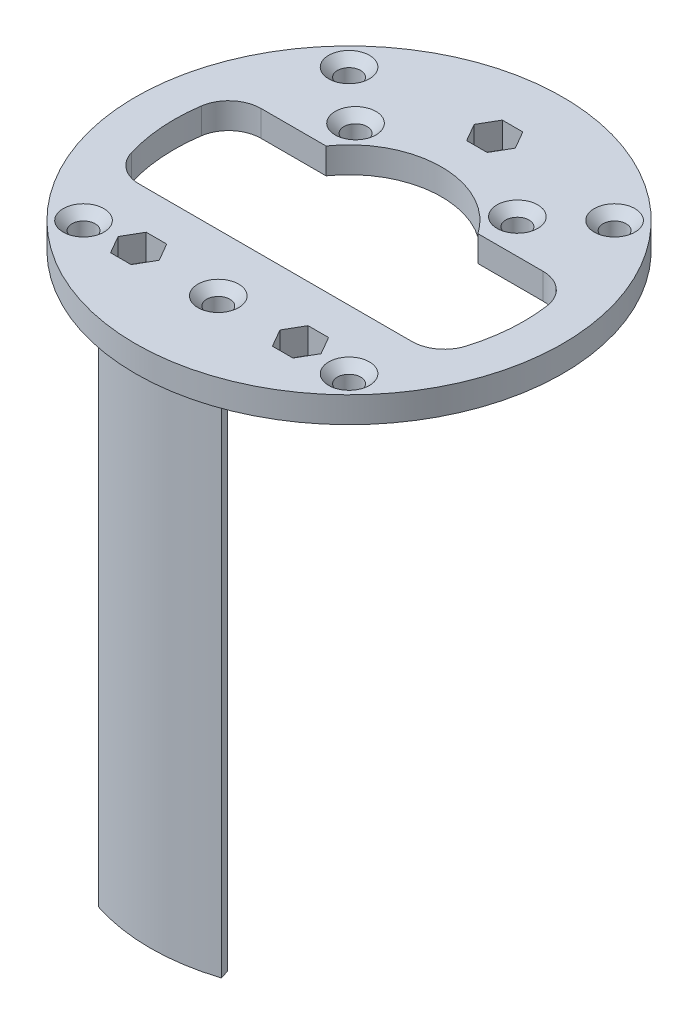
SolidWorks part; units mm, degrees
material "PEI"
ref_plane "Front Plane" through (0, 0, 0) normal (0, 0, 1) x (1, 0, 0)
ref_plane "Top Plane" through (0, 0, 0) normal (0, 1, 0) x (1, 0, 0)
ref_plane "Right Plane" through (0, 0, 0) normal (1, 0, 0) x (0, 0, -1)
sketch "Sketch1" plane through (0, 0, 0) normal (0, 1, 0) x (1, 0, 0)
  circle A0 centre (0, 0) radius 33
  circle A1 centre (0, 0) radius 27
  dimension "D1" = 66
  dimension "D2" = 6
extrude "Boss-Extrude1" add sketch "Sketch1" along normal blind 4
sketch "Sketch2" plane through (0, 4, 0) normal (0, 1, 0) x (1, 0, 0)
  line L0 (-24.5, -11.3468) -> (24.5, -11.3468)
  line L1 (-25.7325, 8.1755) -> (-11.7325, 8.1755)
  line L2 (0, 0) -> (7.7557, 0) construction
  line L3 (11.7325, 8.1755) -> (25.7325, 8.1755)
  line L4 (-20.5061, 20.5061) -> (0, 0) construction
  line L5 (-12.5, 13.5) -> (12.5, 13.5) construction
  circle A0 centre (0, 22.5) radius 2.25 construction
  circle A1 centre (-12.5, -20) radius 2.25 construction
  circle A2 centre (12.5, -20) radius 2.25 construction
  circle A4 centre (-12.5, 13.5) radius 1.5
  circle A6 centre (0, 0) radius 27 construction
  arc A8 (-11.7325, 8.1755) -> (11.7325, 8.1755) centre (0, 0) cw
  arc A9 (25.7325, 8.1755) -> (-25.7325, 8.1755) centre (0, 0) ccw
  arc A10 (24.5, -11.3468) -> (-24.5, -11.3468) centre (0, 0) cw
  circle A11 centre (12.5, 13.5) radius 1.5
  circle A12 centre (0, 0) radius 29 construction
  circle A13 centre (0, 0) radius 33 construction
  circle A14 centre (-20.5061, 20.5061) radius 1.75 construction
  circle A15 centre (20.5061, 20.5061) radius 1.75 construction
  circle A16 centre (20.5061, -20.5061) radius 1.75 construction
  circle A17 centre (-20.5061, -20.5061) radius 1.75 construction
  circle A18 centre (0, -20.2) radius 1.5
  point P15 (0, 13.5)
  point P19 (0, 0)
  point P44 (0, 0)
  circle M2 centre (0, 0) radius 27
  dimension "D5" = 4.5
  dimension "D6" = 4.5
  dimension "D7" = 4.5
  dimension "D12" = 14.3
  dimension "D16" = 3.5
  dimension "D11" = 3
  dimension "D1" = 25
  dimension "D2" = 12.5
  dimension "D3" = 22.5
  dimension "D4" = 20
  dimension "D14" = 4
  dimension "D15" = 135
  dimension "D8" = 14
  dimension "D9" = 14
  dimension "D10" = 49
  dimension "D18" = 25
  dimension "D19" = 20.2
  dimension "D13" = 13.5
  dimension "D17" = 4
extrude "Saliente-Extruir1" add sketch "Sketch2" against normal up to surface (4 mm away) contours L1 A8 L3 M2 | L0 M2 up to face at (0, 0, 33)
sketch "Croquis1" plane through (0, 4, 0) normal (0, 1, 0) x (1, 0, 0)
  line L1 (-9.3246, -20) -> (-10.9123, -17.25)
  line L2 (-10.9123, -17.25) -> (-14.0877, -17.25)
  line L3 (-14.0877, -17.25) -> (-15.6754, -20)
  line L4 (-15.6754, -20) -> (-14.0877, -22.75)
  line L5 (-14.0877, -22.75) -> (-10.9123, -22.75)
  line L6 (-10.9123, -22.75) -> (-9.3246, -20)
  line L7 (15.6754, -20) -> (14.0877, -17.25)
  line L8 (14.0877, -17.25) -> (10.9123, -17.25)
  line L9 (10.9123, -17.25) -> (9.3246, -20)
  line L10 (9.3246, -20) -> (10.9123, -22.75)
  line L11 (10.9123, -22.75) -> (14.0877, -22.75)
  line L12 (14.0877, -22.75) -> (15.6754, -20)
  line L13 (3.1754, 22.5) -> (1.5877, 25.25)
  line L14 (1.5877, 25.25) -> (-1.5877, 25.25)
  line L15 (-1.5877, 25.25) -> (-3.1754, 22.5)
  line L16 (-3.1754, 22.5) -> (-1.5877, 19.75)
  line L17 (-1.5877, 19.75) -> (1.5877, 19.75)
  line L18 (1.5877, 19.75) -> (3.1754, 22.5)
  circle A0 centre (-20.5061, 20.5061) radius 1.75 construction
  circle A1 centre (-20.5061, 20.5061) radius 1.75
  circle A4 centre (20.5061, 20.5061) radius 1.75 construction
  circle A5 centre (20.5061, 20.5061) radius 1.75
  circle A6 centre (-12.5, -20) radius 2.75 construction
  circle A7 centre (12.5, -20) radius 2.75 construction
  circle A8 centre (0, 22.5) radius 2.75 construction
  circle A16 centre (-20.5061, -20.5061) radius 1.75 construction
  circle A17 centre (-20.5061, -20.5061) radius 1.75
  circle A18 centre (20.5061, -20.5061) radius 1.75 construction
  circle A19 centre (20.5061, -20.5061) radius 1.75
  dimension "D1" = 5.5
  dimension "D2" = 5.5
  dimension "D3" = 5.5
extrude "Cortar-Extruir1" cut sketch "Croquis1" against normal up to next
hole_wizard "CSK for M3 Flat Head Machine Screw1" positions "Sketch4" profile "Sketch5" countersink size "M3" standard "ANSI Metric" end condition through all
sketch "Sketch4" plane through (0, 4, 0) normal (0, 1, 0) x (1, 0, 0)
  point P0 (-20.5061, 20.5061)
  point P3 (20.5061, 20.5061)
  point P6 (20.5061, -20.5061)
  point P9 (-20.5061, -20.5061)
sketch "Sketch5" plane through (-20.5061, 4, -20.5061) normal (1, 0, 0) x (0, 0, 1)
  line L0 (0, 0) -> (0, 4)
  line L1 (0, 4) -> (1.8, 4)
  line L2 (1.8, 4) -> (1.8, 1.35)
  line L3 (1.8, 1.35) -> (3.15, 0)
  line L5 (3.15, 0) -> (0, 0)
  line L6 (-1.8, 1.35) -> (-3.15, 0) construction
  line L11 (0, -6.35) -> (0, 107.95) construction
  dimension "Thru Hole Dia." = 3.6
  dimension "Thru Hole Depth" = 4
  dimension "Near C'Sink Dia." = 6.3
  dimension "Near C'Sink Angle" = 90
hole_wizard "CSK for M3 Flat Head Machine Screw2" positions "Sketch6" profile "Sketch7" countersink size "M3" standard "ANSI Metric" end condition through all
sketch "Sketch6" plane through (0, 4, 0) normal (0, 1, 0) x (1, 0, 0)
  point P12 (-12.5, 13.5)
  point P15 (12.5, 13.5)
  point P18 (0, -20.2)
sketch "Sketch7" plane through (-12.5, 4, -13.5) normal (1, 0, 0) x (0, 0, 1)
  line L0 (0, 0) -> (0, 4)
  line L1 (0, 4) -> (1.8, 4)
  line L2 (1.8, 4) -> (1.8, 1.35)
  line L3 (1.8, 1.35) -> (3.15, 0)
  line L5 (3.15, 0) -> (0, 0)
  line L6 (-1.8, 1.35) -> (-3.15, 0) construction
  line L11 (0, -6.35) -> (0, 107.95) construction
  dimension "Thru Hole Dia." = 3.6
  dimension "Thru Hole Depth" = 4
  dimension "Near C'Sink Dia." = 6.3
  dimension "Near C'Sink Angle" = 90
fillet "Fillet1" radius 5 4 edges at (-25.7325, 2, -8.1755) (25.7325, 2, -8.1755) (24.5, 2, 11.3468) (-24.5, 2, 11.3468)
sketch "Sketch8" plane through (0, 0, 0) normal (0, -1, 0) x (-1, 0, 0)
  line L0 (0, 0) -> (9.4868, -29.1974) construction
  line L1 (0, 0) -> (-9.4868, -29.1974) construction
  line L2 (-9.4868, -29.1974) -> (-9.0233, -27.7709)
  line L3 (9.4868, -29.1974) -> (9.0233, -27.7709)
  line L4 (0, 0) -> (0, -16.5239) construction
  arc A0 (9.4868, -29.1974) -> (-9.4868, -29.1974) centre (0, 0) cw
  arc A1 (9.0233, -27.7709) -> (-9.0233, -27.7709) centre (0, 0) cw
  circle A2 centre (0, 0) radius 33 construction
  dimension "D1" = 2.3
  dimension "D2" = 1.5
  dimension "D3" = 18
  dimension "D4" = 18
extrude "Boss-Extrude2" add sketch "Sketch8" along normal blind 78
fillet "Fillet2" radius 2 1 edges at (0, 0, 29.2)
equation "\"D2@Sketch2\"=\"D1@Sketch2\"/2"
equation "\"D6@Sketch2\"=\"D5@Sketch2\""
equation "\"D7@Sketch2\"=\"D6@Sketch2\""
equation "\"D2@Croquis1\"=\"D3@Croquis1\""
equation "\"D1@Croquis1\"=\"D3@Croquis1\""
equation "\"D4@Sketch8\"=\"D3@Sketch8\""
